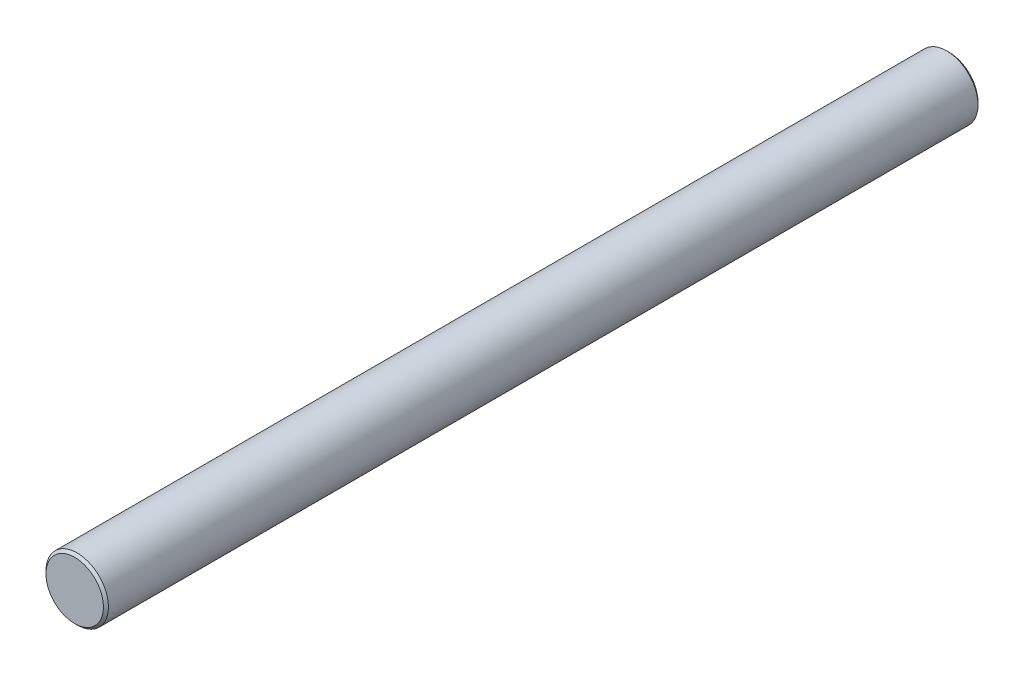
SolidWorks part; units mm, degrees
ref_plane "Ebene vorne" through (0, 0, 0) normal (0, 0, 1) x (1, 0, 0)
ref_plane "Ebene oben" through (0, 0, 0) normal (0, 1, 0) x (1, 0, 0)
ref_plane "Ebene rechts" through (0, 0, 0) normal (1, 0, 0) x (0, 0, -1)
sketch "Skizze1" plane through (0, 0, 0) normal (0, 0, 1) x (1, 0, 0)
  circle A0 centre (0, 0) radius 5
  dimension "D1" = 10
extrude "Aufsatz-Linear austragen1" add sketch "Skizze1" along normal blind 140
chamfer "Fase1" distance 0.4 angle 45 2 edges at (5, 0, 0) (5, 0, 140)
